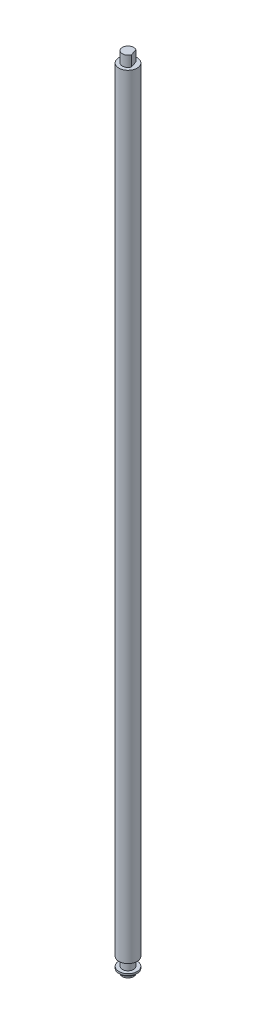
SolidWorks part; units mm, degrees
ref_plane "Plan de face" through (0, 0, 0) normal (0, 0, 1) x (1, 0, 0)
ref_plane "Plan de dessus" through (0, 0, 0) normal (0, 1, 0) x (1, 0, 0)
ref_plane "Plan de droite" through (0, 0, 0) normal (1, 0, 0) x (0, 0, -1)
sketch "Esquisse1" plane through (0, 0, 0) normal (0, 0, 1) x (1, 0, 0)
  line L0 (0, 0) -> (0, 413)
  line L1 (0, 413) -> (2.9, 413)
  line L2 (2.9, 413) -> (2.9, 407.5)
  line L3 (2.9, 407.5) -> (4.7, 407.5)
  line L4 (4.7, 407.5) -> (4.7, 7.7)
  line L5 (4.7, 7.7) -> (2.9, 7.7)
  line L6 (2.9, 7.7) -> (2.9, 3.2)
  line L7 (2.9, 3.2) -> (4.7, 3.2)
  line L8 (4.7, 1.5) -> (4.7, 3.2)
  line L10 (2.9, 0) -> (0, 0)
  line L11 (4.7, 1.5) -> (2.9, 1.5)
  line L12 (2.9, 1.5) -> (2.9, 0)
  dimension "D1" = 4.7
  dimension "D2" = 2.9
  dimension "D3" = 1.7
  dimension "D4" = 1.5
  dimension "D5" = 4.5
  dimension "D6" = 5.5
  dimension "D7" = 413
revolve "Révolution1" add sketch "Esquisse1" angle 360 about L0
chamfer "Chanfrein1" distance 0.8 angle 45 1 edges at (4.7, 1.5, 0)
sketch "Esquisse2" plane through (0, 413, 0) normal (0, 1, 0) x (1, 0, 0)
  line L0 (1.6271, 2.4005) -> (2.7523, -0.9137)
  line L1 (1.6271, 2.4005) -> (3.521, 3.0435)
  line L2 (2.7523, -0.9137) -> (4.6461, -0.2708)
  line L3 (3.521, 3.0435) -> (4.6461, -0.2708)
  circle A0 centre (0, 0) radius 2.9 construction
  dimension "D1" = 3.5
  dimension "D2" = 2
extrude "Enlèv. mat.-Extru.1" cut sketch "Esquisse2" against normal blind 5.5
